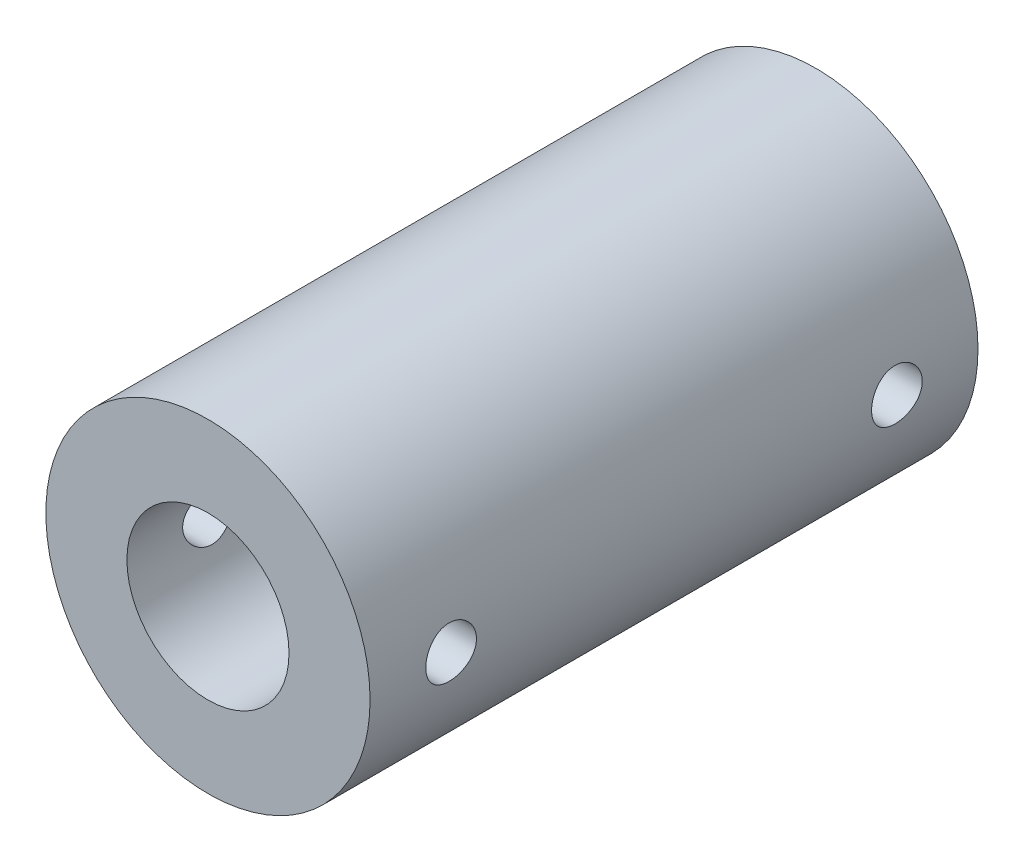
SolidWorks part; units mm, degrees
material "POM generico"
ref_plane "Piano frontale" through (0, 0, 0) normal (0, 0, 1) x (1, 0, 0)
ref_plane "Piano superiore" through (0, 0, 0) normal (0, 1, 0) x (1, 0, 0)
ref_plane "Piano destro" through (0, 0, 0) normal (1, 0, 0) x (0, 0, -1)
sketch "Schizzo1" plane through (0, 0, 0) normal (0, 0, 1) x (1, 0, 0)
  circle A0 centre (0, 0) radius 8
  dimension "D1" = 16
extrude "Estrusione-Estrusione1" add sketch "Schizzo1" along normal blind 30
sketch "Schizzo2" plane through (0, 0, 30) normal (0, 0, 1) x (1, 0, 0)
  circle A0 centre (0, 0) radius 2.5
extrude "Taglio-Estrusione1" cut sketch "Schizzo2" against normal through all
sketch "Schizzo3" plane through (0, 0, 30) normal (0, 0, 1) x (1, 0, 0)
  circle A0 centre (0, 0) radius 4
  dimension "D1" = 8
extrude "Taglio-Estrusione2" cut sketch "Schizzo3" against normal blind 15
sketch "Schizzo4" plane through (0, 0, 0) normal (1, 0, 0) x (0, 0, -1)
  line L0 (-30, 8) -> (-30, -8) construction
  line L1 (0, -8) -> (0, 8) construction
  circle A0 centre (-26, 0) radius 1.25
  circle A1 centre (-4, 0) radius 1.25
  dimension "D3" = 2.5
  dimension "D4" = 2.5
  dimension "D1" = 4
  dimension "D2" = 4
extrude "Taglio-Estrusione3" cut sketch "Schizzo4" against normal through all and the other way through all
